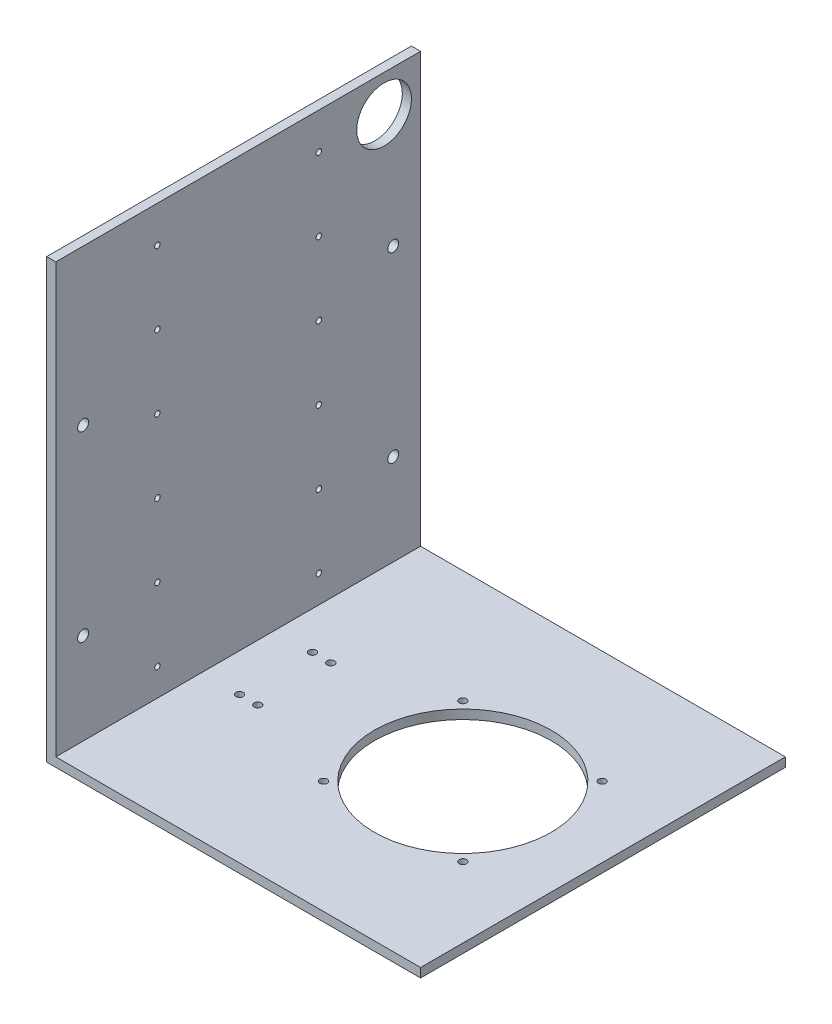
SolidWorks part; units mm, degrees
ref_plane "Front Plane" through (0, 0, 0) normal (0, 0, 1) x (1, 0, 0)
ref_plane "Top Plane" through (0, 0, 0) normal (0, 1, 0) x (1, 0, 0)
ref_plane "Right Plane" through (0, 0, 0) normal (1, 0, 0) x (0, 0, -1)
sketch "Sketch1" plane through (0, 0, 0) normal (0, 0, 1) x (1, 0, 0)
  line L0 (0, 240) -> (0, 0)
  line L1 (0, 0) -> (205, 0)
  line L2 (205, 0) -> (205, 5)
  line L3 (205, 5) -> (5, 5)
  line L4 (5, 5) -> (5, 240)
  line L5 (5, 240) -> (0, 240)
  dimension "D1" = 5
  dimension "D2" = 5
  dimension "D3" = 200
  dimension "D4" = 235
extrude "Boss-Extrude1" add sketch "Sketch1" along normal blind 200
sketch "Sketch2" plane through (0, 5, 0) normal (0, 1, 0) x (1, 0, 0)
  line L0 (205, -100) -> (0, -100) construction
  line L1 (205, -200) -> (205, 0) construction
  line L2 (0, -200) -> (0, 0) construction
  line L4 (166.3526, -138.1825) -> (89.9826, -138.1825) construction
  line L5 (166.3526, -138.1825) -> (166.3526, -61.8175) construction
  line L6 (166.3526, -61.8175) -> (89.9826, -61.8175) construction
  line L7 (89.9826, -138.1825) -> (89.9826, -61.8175) construction
  line L8 (166.3526, -138.1825) -> (89.9826, -61.8175) construction
  line L9 (166.3526, -61.8175) -> (89.9826, -138.1825) construction
  circle A0 centre (128.1676, -100) radius 48.5
  circle A1 centre (89.9826, -61.8175) radius 2
  circle A2 centre (166.3526, -61.8175) radius 2
  circle A3 centre (89.9826, -138.1825) radius 2
  circle A4 centre (166.3526, -138.1825) radius 2
  dimension "D1" = 97
  dimension "D2" = 4
  dimension "D3" = 108
  dimension "D4" = 76.37
extrude "Cut-Extrude1" cut sketch "Sketch2" against normal up to next
sketch "Sketch3" plane through (0, 5, 0) normal (0, 1, 0) x (1, 0, 0)
  line L0 (30.75, 0) -> (30.75, -200) construction
  line L1 (205, 0) -> (5, 0) construction
  line L2 (205, -200) -> (5, -200) construction
  line L3 (30.75, -200) -> (30.75, -71.2391) construction
  line L4 (-16.5042, -100) -> (30.75, -100) construction
  line L6 (5, -200) -> (5, 0) construction
  circle A0 centre (25.75, -80) radius 2
  circle A1 centre (25.75, -120) radius 2
  circle A2 centre (35.75, -120) radius 2
  circle A3 centre (35.75, -80) radius 2
  point P10 (7.1229, -100)
  dimension "D2" = 40
  dimension "D3" = 10
  dimension "D4" = 4
  dimension "D1" = 25.75
extrude "Cut-Extrude2" cut sketch "Sketch3" against normal up to next
sketch "Sketch4" plane through (5, 0, 0) normal (1, 0, 0) x (0, 0, -1)
  line L0 (0, 5) -> (0, 240) construction
  line L1 (-200, 240) -> (0, 240) construction
  circle A0 centre (-20, 220) radius 15
  dimension "D1" = 30
  dimension "D2" = 20
  dimension "D3" = 20
extrude "Cut-Extrude3" cut sketch "Sketch4" against normal blind 10
sketch "Sketch5" plane through (5, 0, 0) normal (1, 0, 0) x (0, 0, -1)
  line L0 (-100, 240) -> (-100, 5) construction
  line L1 (-200, 240) -> (0, 240) construction
  line L2 (-200, 5) -> (0, 5) construction
  line L3 (-185, 240) -> (-185, 5) construction
  line L4 (-200, 5) -> (-200, 240) construction
  circle A0 centre (-185, 55) radius 3
  circle A1 centre (-185, 155) radius 3
  circle A2 centre (-15, 55) radius 3
  circle A3 centre (-15, 155) radius 3
  dimension "D2" = 100
  dimension "D3" = 6
  dimension "D1" = 50
  dimension "D4" = 15
extrude "Cut-Extrude4" cut sketch "Sketch5" against normal up to next
sketch "Sketch6" plane through (5, 0, 0) normal (1, 0, 0) x (0, 0, -1)
  line L0 (-100, 240) -> (-100, 5) construction
  line L1 (-200, 240) -> (0, 240) construction
  line L2 (-200, 5) -> (0, 5) construction
  circle A0 centre (-144.25, 220) radius 1.5
  circle A1 centre (-55.75, 220) radius 1.5
  circle A2 centre (-144.25, 180) radius 1.5
  circle A3 centre (-55.75, 180) radius 1.5
  circle A4 centre (-144.25, 140) radius 1.5
  circle A5 centre (-55.75, 140) radius 1.5
  circle A6 centre (-144.25, 100) radius 1.5
  circle A7 centre (-55.75, 100) radius 1.5
  circle A8 centre (-144.25, 60) radius 1.5
  circle A9 centre (-55.75, 60) radius 1.5
  circle A10 centre (-144.25, 20) radius 1.5
  circle A11 centre (-55.75, 20) radius 1.5
  dimension "D1" = 88.5
  dimension "D2" = 20
  dimension "D3" = 3
  dimension "D5" = 40
  dimension "D4" = 6
extrude "Cut-Extrude5" cut sketch "Sketch6" against normal up to next
